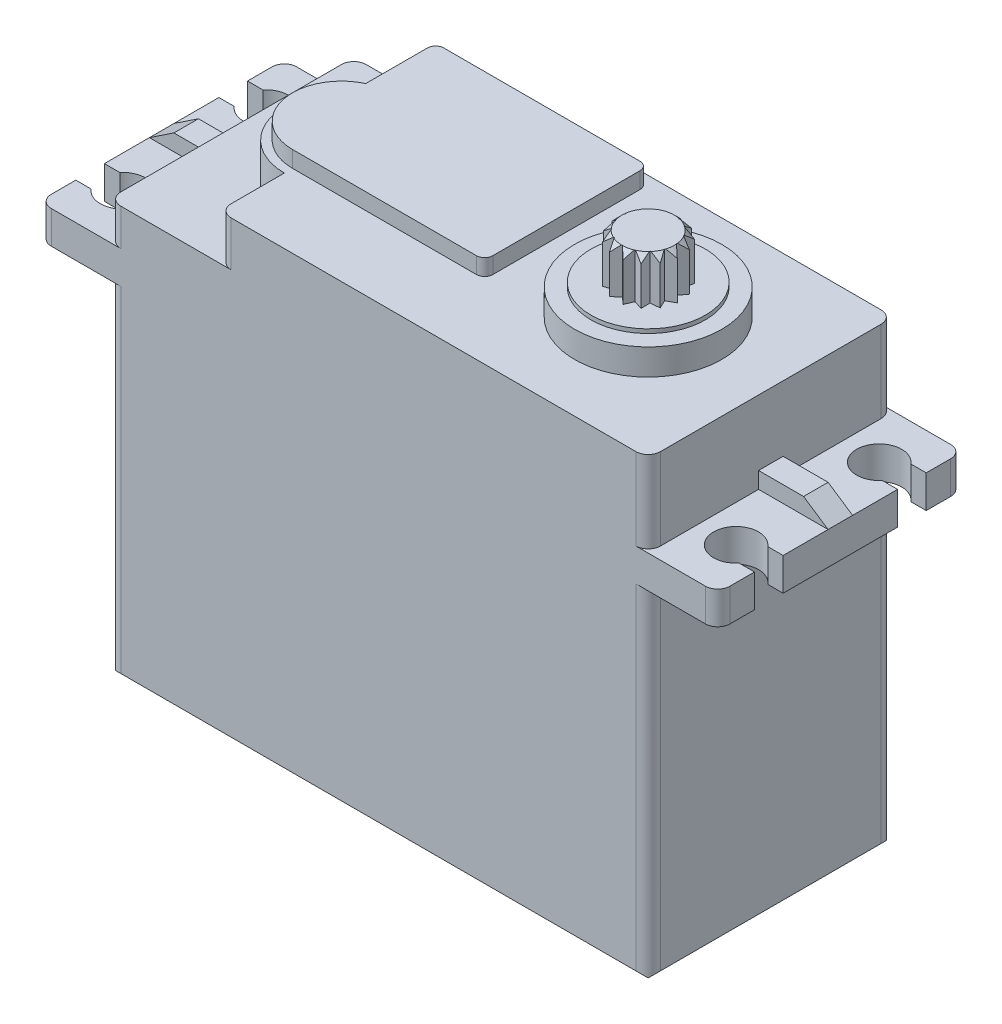
SolidWorks part; units mm, degrees
ref_plane "Front Plane" through (0, 0, 0) normal (0, 0, 1) x (1, 0, 0)
ref_plane "Top Plane" through (0, 0, 0) normal (0, 1, 0) x (1, 0, 0)
ref_plane "Right Plane" through (0, 0, 0) normal (1, 0, 0) x (0, 0, -1)
sketch "Sketch1" plane through (0, 0, 0) normal (0, 1, 0) x (1, 0, 0)
  line L1 (0, 0) -> (66, 0)
  line L2 (0, 0) -> (0, 30)
  line L3 (0, 30) -> (66, 30)
  line L4 (66, 0) -> (66, 30)
  dimension "D1" = 66
  dimension "D2" = 30
extrude "Boss-Extrude1" add sketch "Sketch1" along normal blind 56
chamfer "Chamfer1" distance 1 4 edges at (33, 0, 0) (66, 0, -15) (33, 0, -30) (0, 0, -15)
ref_plane "Plane1" through (0, 42, 0) normal (0, 1, 0) x (1, 0, 0)
sketch "Sketch3" plane through (0, 42, 0) normal (0, 1, 0) x (1, 0, 0)
  line L0 (0, 30) -> (0, 0) construction
  line L1 (0, 30) -> (-8.5, 30)
  line L2 (0, 30) -> (0, 0)
  line L3 (0, 0) -> (-8.5, 0)
  line L4 (-8.5, 30) -> (-8.5, 0)
  line L5 (66, 30) -> (0, 30) construction
  line L6 (0, 0) -> (66, 0) construction
  dimension "D1" = 8.5
extrude "Boss-Extrude2" add sketch "Sketch3" along normal blind 4
sketch "Sketch4" plane through (0, 46, 0) normal (0, 1, 0) x (1, 0, 0)
  line L0 (-4.5, 23.75) -> (-4.5, 6.25) construction
  line L1 (-8.5, 30) -> (-8.5, 0) construction
  line L2 (-8.5, 8) -> (-6.6213, 8)
  line L3 (-8.5, 8) -> (-8.5, 4.5)
  line L4 (-8.5, 4.5) -> (-6.6213, 4.5)
  line L5 (-4.5, 6.25) -> (-8.5, 6.25) construction
  line L6 (-4.5, 23.75) -> (-8.5, 23.75) construction
  line L7 (-8.5, 25.5) -> (-6.6213, 25.5)
  line L8 (-8.5, 25.5) -> (-8.5, 22)
  line L9 (-8.5, 22) -> (-6.6213, 22)
  line L11 (-8.5, 15) -> (0, 15) construction
  line L12 (0, 0) -> (0, 30) construction
  arc A0 (-6.6213, 4.5) -> (-6.6213, 8) centre (-4.5, 6.25) ccw
  arc A1 (-6.6213, 22) -> (-6.6213, 25.5) centre (-4.5, 23.75) ccw
  point P15 (0, 0)
  point P19 (0, 0)
  point P20 (-4.5, 15)
  dimension "D4" = 2.75
  dimension "D5" = 2.75
  dimension "D1" = 3.5
  dimension "D2" = 3.5
  dimension "D3" = 14
  dimension "D6" = 4
extrude "Cut-Extrude1" cut sketch "Sketch4" against normal up to next
ref_plane "Plane2" through (0, 0, -15) normal (0, 0, 1) x (1, 0, 0)
sketch "Sketch5" plane through (0, 0, -15) normal (0, 0, 1) x (1, 0, 0)
  line L0 (-8.5, 46) -> (0, 46)
  line L1 (0, 46) -> (0, 48)
  line L2 (0, 48) -> (-5.5, 48)
  line L3 (-5.5, 48) -> (-8.5, 46)
  line L4 (-8.5, 46) -> (0, 46) construction
  line L5 (0, 56) -> (0, 46) construction
  line L6 (-8.5, 46) -> (-8.5, 42) construction
  point P2 (0, 0)
  point P9 (0, 0)
  point P12 (-6.0502, 48.3675)
  point P13 (-4.4007, 49.5)
  dimension "D1" = 2
  dimension "D2" = 3
extrude "Boss-Extrude3" add sketch "Sketch5" along normal mid plane 3
fillet "Fillet2" radius 1.5 2 edges at (-8.5, 44, 0) (-8.5, 44, -30)
ref_plane "Plane3" through (33, 0, 0) normal (-1, 0, 0) x (0, 0, 1)
mirror "Mirror1" about plane through (33, 0, 0) normal (-1, 0, 0) of "Cut-Extrude1", "Fillet2", "Boss-Extrude2", "Boss-Extrude3"
sketch "Sketch6" plane through (0, 56, 0) normal (0, 1, 0) x (1, 0, 0)
  line L0 (13.5, 0) -> (13.5, 8)
  line L1 (0, 30) -> (10, 30)
  line L2 (0, 30) -> (0, 0)
  line L3 (0, 0) -> (13.5, 0)
  line L5 (0, 30) -> (0, 0) construction
  line L6 (66, 30) -> (0, 30) construction
  line L7 (0, 0) -> (66, 0) construction
  line L9 (10, 21.0622) -> (10, 30)
  arc A0 (10, 21.0622) -> (13.5, 8) centre (13.5, 15) ccw
  dimension "D2" = 7
  dimension "D1" = 8
  dimension "D3" = 10
  dimension "D4" = 13.5
extrude "Cut-Extrude2" cut sketch "Sketch6" against normal blind 5.5
fillet "Fillet3" radius 1.5 10 edges at (10, 53.25, -30) (0, 48.25, -30) (0, 21.5, -30) (66, 51, -30) (66, 21.5, -30) (66, 51, 0) (66, 21.5, 0) (13.5, 53.25, 0) (0, 48.25, 0) (0, 21.5, 0)
sketch "Sketch7" plane through (0, 56, 0) normal (0, 1, 0) x (1, 0, 0)
  line L0 (13.5, 9) -> (37, 9)
  line L1 (37, 9) -> (37, 29)
  line L2 (37, 29) -> (11, 29)
  line L3 (11, 29) -> (11, 20.4544)
  line L4 (64.5, 30) -> (11.5, 30) construction
  line L5 (10, 21.0622) -> (10, 28.5) construction
  line L6 (-30.25, 15) -> (30.25, 15) construction
  line L7 (13.5, 1.5) -> (13.5, 8) construction
  arc A0 (11, 20.4544) -> (13.5, 9) centre (13.5, 15) ccw
  point P1 (14.3522, 15.456)
  point P12 (13.7222, 15)
  point P15 (0, 0)
  dimension "D1" = 1
  dimension "D2" = 1
  dimension "D3" = 1
  dimension "D4" = 26
extrude "Boss-Extrude4" add sketch "Sketch7" along normal blind 2
fillet "Fillet4" radius 1 3 edges at (11, 57, -29) (37, 57, -29) (37, 57, -9)
sketch "Sketch8" plane through (0, 56, 0) normal (0, 1, 0) x (1, 0, 0)
  line L0 (-30.25, 15) -> (30.25, 15) construction
  line L1 (60, 21.9847) -> (60, 7.9445) construction
  line L2 (66, 1.5) -> (66, 28.5) construction
  circle A0 centre (51, 15) radius 9
  dimension "D1" = 18
  dimension "D2" = 6
extrude "Boss-Extrude5" add sketch "Sketch8" along normal blind 3.2
sketch "Sketch9" plane through (0, 59.2, 0) normal (0, 1, 0) x (1, 0, 0)
  circle A0 centre (51, 15) radius 7
  circle A1 centre (51, 15) radius 9 construction
  dimension "D1" = 14
extrude "Boss-Extrude6" add sketch "Sketch9" along normal blind 0.5
sketch "Sketch10" plane through (0, 59.7, 0) normal (0, 1, 0) x (1, 0, 0)
  line L0 (51, 19) -> (51, 15) construction
  line L1 (50.25, 17.9289) -> (51, 19)
  line L2 (51, 19) -> (51.75, 17.9289)
  line L3 (50.25, 17.9289) -> (51.75, 17.9289) construction
  line L4 (50.25, 17.9289) -> (50.25, 15)
  line L5 (50.25, 15) -> (51.75, 15)
  line L6 (51.75, 15) -> (51.75, 17.9289)
  circle A2 centre (51, 15) radius 7 construction
  point P2 (51, 17.9289)
  point P7 (50.5155, 17.9754)
  dimension "D1" = 4
  dimension "D2" = 70
  dimension "D3" = 1.5
extrude "Boss-Extrude8" add sketch "Sketch10" along normal blind 5.5
pattern_circular "CirPattern1" count 15 over 360 about axis through (51, 0, -15) along (0, 1, 0) of "Boss-Extrude8"
ref_plane "Plane4" through (51, 0, 0) normal (-1, 0, 0) x (0, -1, 0)
sketch "Sketch13" plane through (51, 0, 0) normal (-1, 0, 0) x (0, -1, 0)
  line L0 (-65.2, -18.2) -> (-65.2, -19)
  line L1 (-65.2, -19) -> (-64.4, -19)
  line L2 (-64.4, -19) -> (-65.2, -18.2)
  line L3 (-65.2, -19) -> (-59.7, -19) construction
  line L4 (-65.2, -19) -> (-65.2, -18.0685) construction
  dimension "D1" = 45
  dimension "D2" = 0.8
ref_axis "Axis1" through (51, 66.6247, -15) along (0, -1, 0)
revolve "Cut-Revolve1" cut sketch "Sketch13" angle 360 about axis through (51, 66.6247, -15) along (0, -1, 0)
